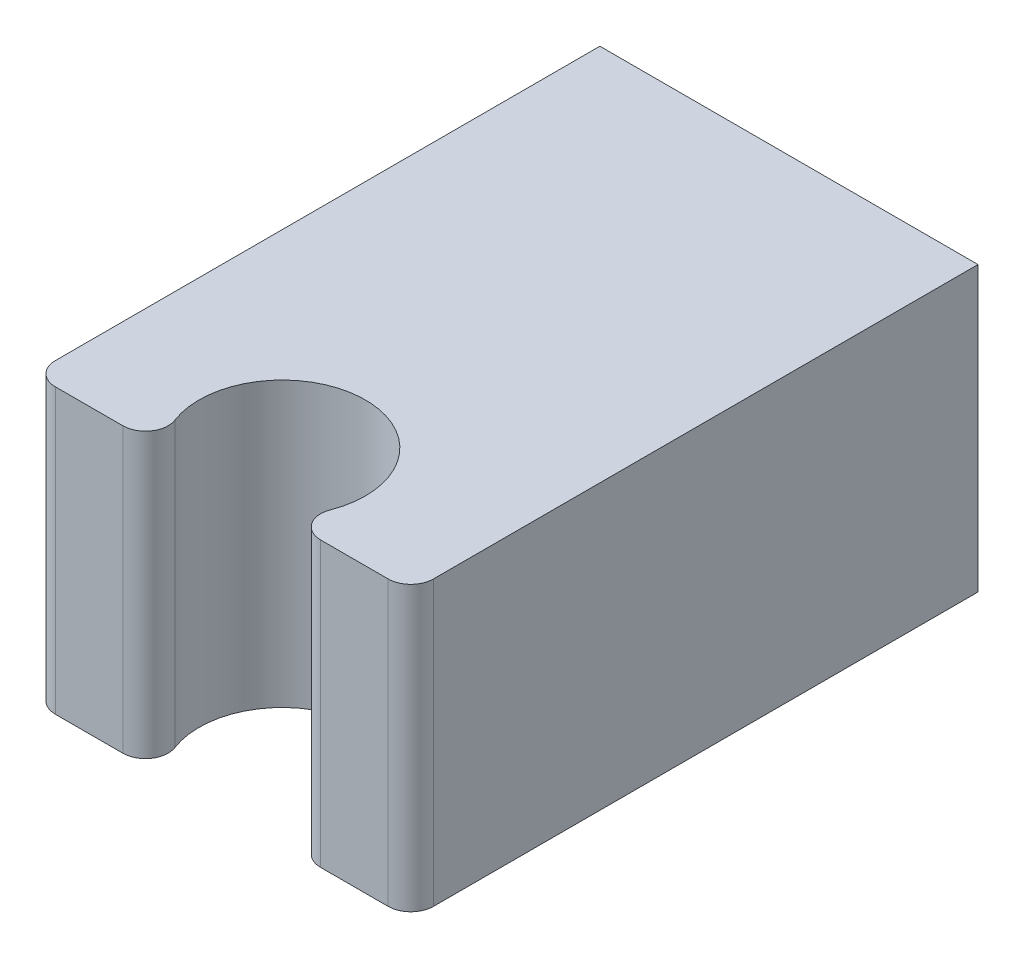
SolidWorks part; units mm, degrees
ref_plane "Front Plane" through (0, 0, 0) normal (1, 0, 0) x (0, 1, 0)
ref_plane "Top Plane" through (0, 0, 0) normal (0, 0, 1) x (0, 1, 0)
ref_plane "Right Plane" through (0, 0, 0) normal (0, 1, 0) x (-1, 0, 0)
sketch "Sketch1" plane through (0, 0, 0) normal (0, 0, 1) x (0, 1, 0)
  line L1 (-3.75, -5) -> (3.75, -5)
  line L2 (-3.75, -5) -> (-3.75, 5)
  line L3 (-3.75, 5) -> (3.75, 5)
  line L4 (3.75, -5) -> (3.75, 5)
  line L5 (-3.75, -5) -> (3.75, 5) construction
  line L6 (-3.75, 5) -> (3.75, -5) construction
  point P0 (0, 0)
extrude "Boss-Extrude1" add sketch "Sketch1" along normal blind 10 and the other way blind 5 contours L4 L3 L2 L1
sketch "Sketch2" plane through (0, 3.75, 0) normal (0, 1, 0) x (-1, 0, 0)
  line L1 (-5, 10) -> (0, 10)
  line L2 (-5, 10) -> (-5, 8.4)
  line L3 (-5, 8.4) -> (0, 8.4)
  line L4 (0, 10) -> (0, 8.4)
  circle A0 centre (0, 8.4) radius 2.2
extrude "Cut-Extrude1" cut sketch "Sketch2" against normal through all contours A0
fillet "Fillet1" radius 0.6 4 edges at (1.51, 0, 10) (-1.51, 0, 10) (-5, 0, 10) (5, 0, 10)
sketch "Sketch3" plane through (0, 3.75, 0) normal (0, 1, 0) x (-1, 0, 0)
  line L0 (-2.0153, 9.4) -> (2.0153, 9.4)
  arc A0 (-2.0549, 9.1857) -> (-2.6153, 10) centre (-2.6153, 9.4) ccw construction
  arc A1 (2.6153, 10) -> (2.0549, 9.1857) centre (2.6153, 9.4) ccw construction
